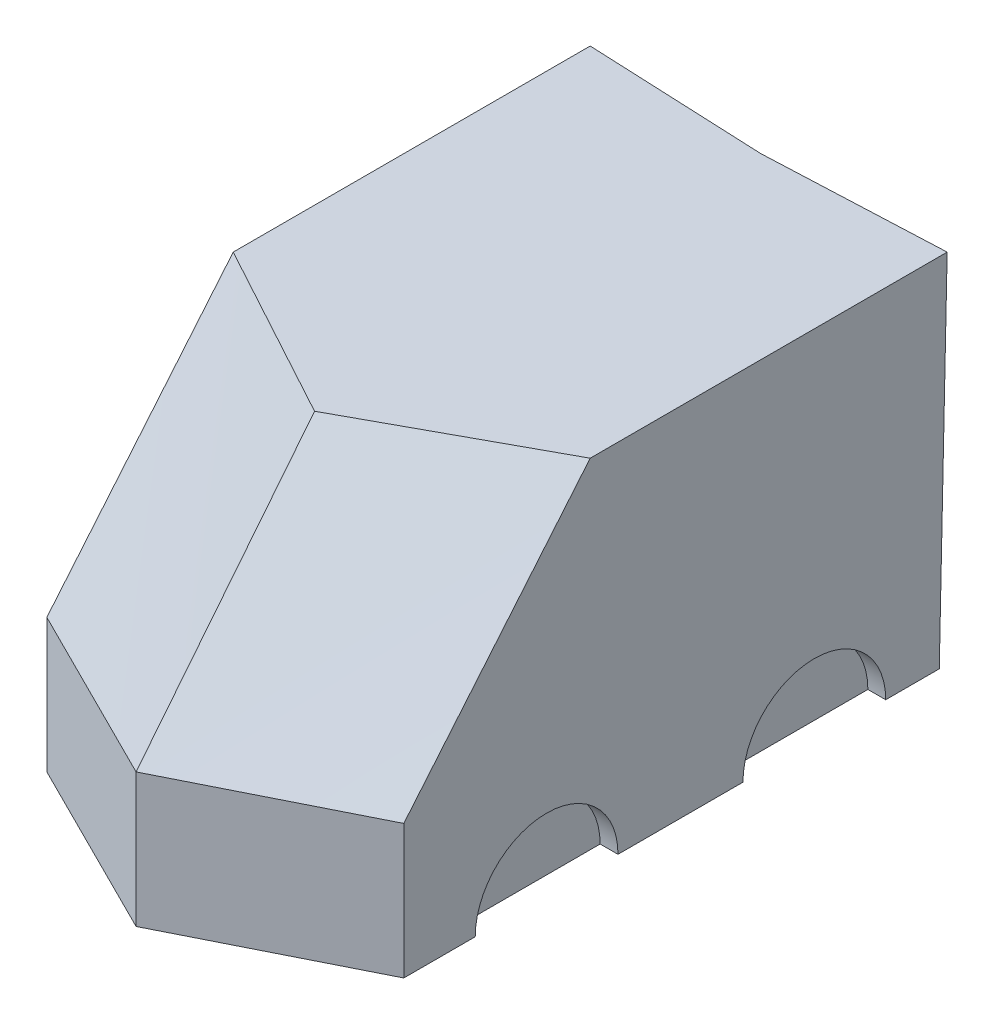
SolidWorks part; units mm, degrees
ref_plane "Front Plane" through (0, 0, 0) normal (0, 0, 1) x (1, 0, 0)
ref_plane "Top Plane" through (0, 0, 0) normal (0, 1, 0) x (1, 0, 0)
ref_plane "Right Plane" through (0, 0, 0) normal (1, 0, 0) x (0, 0, -1)
ref_plane "Plane1" through (100, 0, 0) normal (1, 0, 0) x (0, 0, -1)
sketch "Sketch1" plane through (0, 0, 0) normal (1, 0, 0) x (0, 0, -1)
  line L0 (0, 0) -> (-350, 0)
  line L1 (-350, 0) -> (-350, 75)
  line L2 (-350, 75) -> (-250, 200)
  line L3 (-250, 200) -> (0, 200)
  line L4 (0, 200) -> (0, 0)
  dimension "D1" = 200
  dimension "D2" = 250
  dimension "D3" = 350
  dimension "D4" = 75
sketch "Sketch2" plane through (100, 0, 0) normal (1, 0, 0) x (0, 0, -1)
  line L0 (0, 0) -> (4.4224, 200)
  line L1 (4.4224, 200) -> (-195.5776, 200)
  line L2 (-195.5776, 200) -> (-300, 75)
  line L3 (-300, 75) -> (-300, 0)
  line L4 (-300, 0) -> (0, 0)
  dimension "D1" = 200
  dimension "D2" = 200
  dimension "D3" = 300
  dimension "D4" = 75
loft "Loft1" add profiles "Sketch1", "Sketch2"
sketch "Sketch3" plane through (100, 0, 0) normal (1, 0, 0) x (0, 0, -1)
  line L0 (-300, 0) -> (0, 0) construction
  circle A0 centre (-220, 0) radius 40
  circle A1 centre (-70, 0) radius 40
  dimension "D1" = 80
  dimension "D2" = 80
  dimension "D3" = 70
  dimension "D4" = 150
extrude "Cut-Extrude1" cut sketch "Sketch3" against normal blind 10
mirror "Mirror2" about plane through (0, 0, 0) normal (-1, 0, 0) of "Loft1", "Cut-Extrude1"
